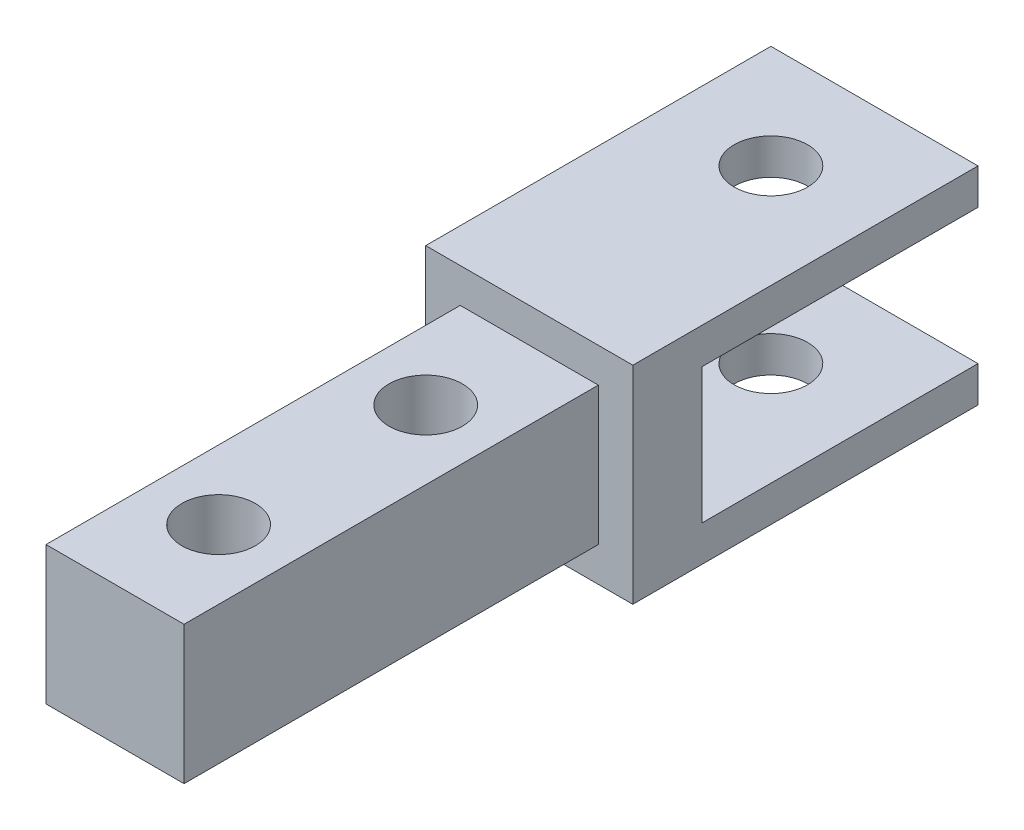
SolidWorks part; units mm, degrees
ref_plane "Front Plane" through (0, 0, 0) normal (0, 0, 1) x (1, 0, 0)
ref_plane "Top Plane" through (0, 0, 0) normal (0, 1, 0) x (1, 0, 0)
ref_plane "Right Plane" through (0, 0, 0) normal (1, 0, 0) x (0, 0, -1)
sketch "Sketch1" plane through (0, 0, 0) normal (0, 0, 1) x (1, 0, 0)
  line L1 (-6.35, -6.35) -> (6.35, -6.35)
  line L2 (-6.35, -6.35) -> (-6.35, 6.35)
  line L3 (-6.35, 6.35) -> (6.35, 6.35)
  line L4 (6.35, -6.35) -> (6.35, 6.35)
  line L5 (-6.35, -6.35) -> (6.35, 6.35) construction
  line L6 (-6.35, 6.35) -> (6.35, -6.35) construction
  point P0 (0, 0)
  dimension "D1" = 12.7
  dimension "D2" = 12.7
extrude "Boss-Extrude1" add sketch "Sketch1" along normal blind 38.1 contours L3 L4 L1 L2
sketch "Sketch2" plane through (0, 0, 0) normal (0, 0, 1) x (1, 0, 0)
  line L1 (-9.525, -9.525) -> (9.525, -9.525)
  line L2 (-9.525, -9.525) -> (-9.525, 9.525)
  line L3 (-9.525, 9.525) -> (9.525, 9.525)
  line L4 (9.525, -9.525) -> (9.525, 9.525)
  line L5 (-9.525, -9.525) -> (9.525, 9.525) construction
  line L6 (-9.525, 9.525) -> (9.525, -9.525) construction
  point P0 (0, 0)
  dimension "D1" = 19.05
  dimension "D2" = 19.05
extrude "Boss-Extrude2" add sketch "Sketch2" against normal blind 31.75
sketch "Sketch3" plane through (-9.525, 0, 0) normal (-1, 0, 0) x (0, 0, 1)
  line L0 (-31.75, 9.525) -> (-31.75, -9.525) construction
  line L1 (-31.75, -6.223) -> (-6.35, -6.223)
  line L2 (-31.75, -6.223) -> (-31.75, 6.223)
  line L3 (-31.75, 6.223) -> (-6.35, 6.223)
  line L4 (-6.35, -6.223) -> (-6.35, 6.223)
  point P6 (-6.35, 0)
  dimension "D1" = 12.446
  dimension "D2" = 25.4
extrude "Cut-Extrude1" cut sketch "Sketch3" against normal through all
fillet "Fillet1" [suppressed] radius 9.525
hole_wizard "1/4 Clearance Hole1" positions "Sketch5" profile "Sketch6" hole size "1/4" standard "ANSI Inch"
sketch "Sketch5" plane through (47.625, 9.525, -52.8225) normal (0, 1, 0) x (0, 0, 1)
  line L0 (30.5975, -47.625) -> (81.3975, -47.625) construction
  line L1 (196.3325, 47.625) -> (196.3325, -47.625) construction
  point P0 (30.5975, -47.625)
  point P3 (62.3475, -47.625)
  point P5 (81.3975, -47.625)
  point P15 (196.3325, -47.625)
sketch "Sketch6" plane through (0, 9.525, -22.225) normal (1, 0, 0) x (0, 0, 1)
  line L0 (0, 0) -> (0, 21.0798)
  line L1 (0, 21.0798) -> (3.3782, 19.05)
  line L2 (3.3782, 19.05) -> (3.3782, 0)
  line L3 (3.3782, 0) -> (0, 0)
  line L4 (0, 21.0798) -> (-3.3782, 19.05) construction
  line L5 (0, -6.35) -> (0, 107.95) construction
  dimension "Hole Dia." = 6.7564
  dimension "Hole Depth" = 19.05
  dimension "Drill Angle" = 118
